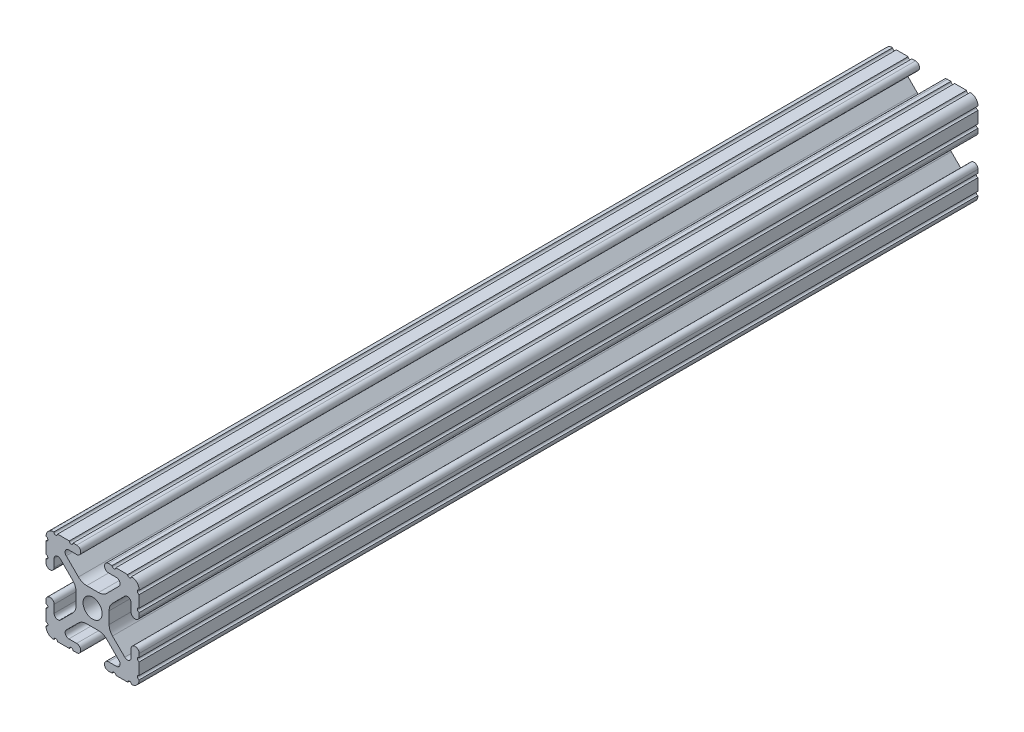
SolidWorks part; units mm, degrees
material "6061 Alloy"
ref_plane "Front Plane" through (0, 0, 0) normal (0, 0, 1) x (1, 0, 0)
ref_plane "Top Plane" through (0, 0, 0) normal (0, 1, 0) x (1, 0, 0)
ref_plane "Right Plane" through (0, 0, 0) normal (1, 0, 0) x (0, 0, -1)
ref_plane "Plane1" through (0, 0, -25.4) normal (0, 0, -1) x (-1, 0, 0)
sketch "Sketch1" plane through (0, 0, -25.4) normal (0, 0, -1) x (-1, 0, 0)
  line L0 (12.7, -9.5504) -> (12.7, -6.3331)
  line L1 (12.7, -5.3171) -> (12.7, -4.3434)
  line L2 (10.4902, -4.3434) -> (10.4902, -6.4748)
  line L3 (8.7558, -7.1932) -> (5.4257, -3.8632)
  line L4 (4.4958, -1.6181) -> (4.4958, 1.6181)
  line L5 (5.4257, 3.8632) -> (8.7558, 7.1932)
  line L6 (10.4902, 6.4748) -> (10.4902, 4.3434)
  line L7 (12.7, 4.3434) -> (12.7, 5.3171)
  line L8 (12.7, 6.3331) -> (12.7, 9.5504)
  line L9 (9.5504, 12.7) -> (6.3331, 12.7)
  line L10 (5.3171, 12.7) -> (4.3434, 12.7)
  line L11 (4.3434, 10.4902) -> (6.4748, 10.4902)
  line L12 (7.1932, 8.7558) -> (3.8632, 5.4257)
  line L13 (1.6181, 4.4958) -> (-1.6181, 4.4958)
  line L14 (-3.8632, 5.4257) -> (-7.1932, 8.7558)
  line L15 (-6.4748, 10.4902) -> (-4.3434, 10.4902)
  line L16 (-4.3434, 12.7) -> (-5.3171, 12.7)
  line L17 (-6.3331, 12.7) -> (-9.5504, 12.7)
  line L18 (-12.7, 9.5504) -> (-12.7, 6.3331)
  line L19 (-12.7, 5.3171) -> (-12.7, 4.3434)
  line L20 (-10.4902, 4.3434) -> (-10.4902, 6.4748)
  line L21 (-8.7558, 7.1932) -> (-5.4257, 3.8632)
  line L22 (-4.4958, 1.6181) -> (-4.4958, -1.6181)
  line L23 (-5.4257, -3.8632) -> (-8.7558, -7.1932)
  line L24 (-10.4902, -6.4748) -> (-10.4902, -4.3434)
  line L25 (-12.7, -4.3434) -> (-12.7, -5.3171)
  line L26 (-12.7, -6.3331) -> (-12.7, -9.5504)
  line L27 (-9.5504, -12.7) -> (-6.3331, -12.7)
  line L28 (-5.3171, -12.7) -> (-4.3434, -12.7)
  line L29 (-4.3434, -10.4902) -> (-6.4748, -10.4902)
  line L30 (-7.1932, -8.7558) -> (-3.8632, -5.4257)
  line L31 (-1.6181, -4.4958) -> (1.6181, -4.4958)
  line L32 (3.8632, -5.4257) -> (7.1932, -8.7558)
  line L33 (6.4748, -10.4902) -> (4.3434, -10.4902)
  line L34 (4.3434, -12.7) -> (5.3171, -12.7)
  line L35 (6.3331, -12.7) -> (9.5504, -12.7)
  arc A0 (12.6998, -10.5664) -> (12.7, -9.5504) centre (12.7, -10.0584) cw
  arc A1 (12.7, -6.3331) -> (12.7, -5.3171) centre (12.7, -5.8251) cw
  arc A2 (12.7, -4.3434) -> (10.4902, -4.3434) centre (11.5951, -4.3434) ccw
  arc A3 (10.4902, -6.4748) -> (8.7558, -7.1932) centre (9.4742, -6.4748) cw
  arc A4 (5.4257, -3.8632) -> (4.4958, -1.6181) centre (7.6708, -1.6181) cw
  arc A5 (4.4958, 1.6181) -> (5.4257, 3.8632) centre (7.6708, 1.6181) cw
  arc A6 (8.7558, 7.1932) -> (10.4902, 6.4748) centre (9.4742, 6.4748) cw
  arc A7 (10.4902, 4.3434) -> (12.7, 4.3434) centre (11.5951, 4.3434) ccw
  arc A8 (12.7, 5.3171) -> (12.7, 6.3331) centre (12.7, 5.8251) cw
  arc A9 (12.7, 9.5504) -> (12.6998, 10.5664) centre (12.7, 10.0584) cw
  arc A10 (12.6998, 10.5664) -> (10.5664, 12.6998) centre (10.5918, 10.5918) ccw
  arc A11 (10.5664, 12.6998) -> (9.5504, 12.7) centre (10.0584, 12.7) cw
  arc A12 (6.3331, 12.7) -> (5.3171, 12.7) centre (5.8251, 12.7) cw
  arc A13 (4.3434, 12.7) -> (4.3434, 10.4902) centre (4.3434, 11.5951) ccw
  arc A14 (6.4748, 10.4902) -> (7.1932, 8.7558) centre (6.4748, 9.4742) cw
  arc A15 (3.8632, 5.4257) -> (1.6181, 4.4958) centre (1.6181, 7.6708) cw
  arc A16 (-1.6181, 4.4958) -> (-3.8632, 5.4257) centre (-1.6181, 7.6708) cw
  arc A17 (-7.1932, 8.7558) -> (-6.4748, 10.4902) centre (-6.4748, 9.4742) cw
  arc A18 (-4.3434, 10.4902) -> (-4.3434, 12.7) centre (-4.3434, 11.5951) ccw
  arc A19 (-5.3171, 12.7) -> (-6.3331, 12.7) centre (-5.8251, 12.7) cw
  arc A20 (-9.5504, 12.7) -> (-10.5664, 12.6998) centre (-10.0584, 12.7) cw
  arc A21 (-10.5664, 12.6998) -> (-12.6998, 10.5664) centre (-10.5918, 10.5918) ccw
  arc A22 (-12.6998, 10.5664) -> (-12.7, 9.5504) centre (-12.7, 10.0584) cw
  arc A23 (-12.7, 6.3331) -> (-12.7, 5.3171) centre (-12.7, 5.8251) cw
  arc A24 (-12.7, 4.3434) -> (-10.4902, 4.3434) centre (-11.5951, 4.3434) ccw
  arc A25 (-10.4902, 6.4748) -> (-8.7558, 7.1932) centre (-9.4742, 6.4748) cw
  arc A26 (-5.4257, 3.8632) -> (-4.4958, 1.6181) centre (-7.6708, 1.6181) cw
  arc A27 (-4.4958, -1.6181) -> (-5.4257, -3.8632) centre (-7.6708, -1.6181) cw
  arc A28 (-8.7558, -7.1932) -> (-10.4902, -6.4748) centre (-9.4742, -6.4748) cw
  arc A29 (-10.4902, -4.3434) -> (-12.7, -4.3434) centre (-11.5951, -4.3434) ccw
  arc A30 (-12.7, -5.3171) -> (-12.7, -6.3331) centre (-12.7, -5.8251) cw
  arc A31 (-12.7, -9.5504) -> (-12.6998, -10.5664) centre (-12.7, -10.0584) cw
  arc A32 (-12.6998, -10.5664) -> (-10.5664, -12.6998) centre (-10.5918, -10.5918) ccw
  arc A33 (-10.5664, -12.6998) -> (-9.5504, -12.7) centre (-10.0584, -12.7) cw
  arc A34 (-6.3331, -12.7) -> (-5.3171, -12.7) centre (-5.8251, -12.7) cw
  arc A35 (-4.3434, -12.7) -> (-4.3434, -10.4902) centre (-4.3434, -11.5951) ccw
  arc A36 (-6.4748, -10.4902) -> (-7.1932, -8.7558) centre (-6.4748, -9.4742) cw
  arc A37 (-3.8632, -5.4257) -> (-1.6181, -4.4958) centre (-1.6181, -7.6708) cw
  arc A38 (1.6181, -4.4958) -> (3.8632, -5.4257) centre (1.6181, -7.6708) cw
  arc A39 (7.1932, -8.7558) -> (6.4748, -10.4902) centre (6.4748, -9.4742) cw
  arc A40 (4.3434, -10.4902) -> (4.3434, -12.7) centre (4.3434, -11.5951) ccw
  arc A41 (5.3171, -12.7) -> (6.3331, -12.7) centre (5.8251, -12.7) cw
  arc A42 (9.5504, -12.7) -> (10.5664, -12.6998) centre (10.0584, -12.7) cw
  arc A43 (10.5664, -12.6998) -> (12.6998, -10.5664) centre (10.5918, -10.5918) ccw
  circle A44 centre (0, 0) radius 2.6035
extrude "Boss-Extrude1" add sketch "Sketch1" against normal blind 228.6
